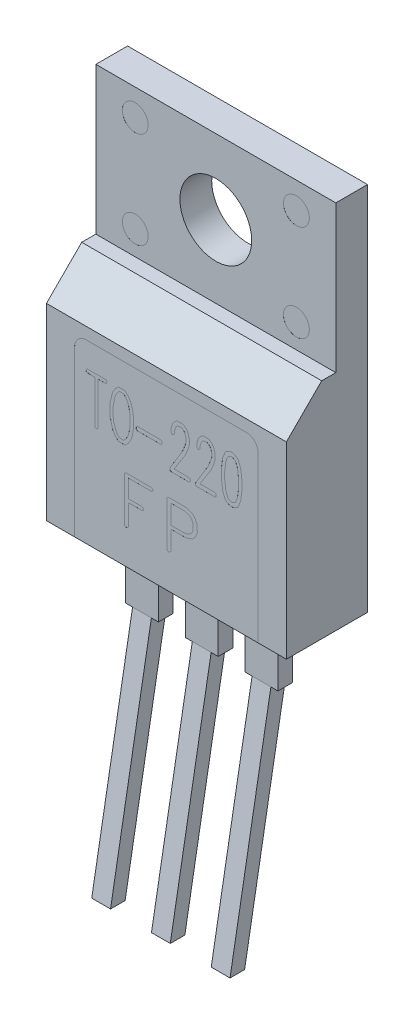
SolidWorks part; units mm, degrees
ref_plane "Front Plane" through (0, 0, 0) normal (0, 0, 1) x (1, 0, 0)
ref_plane "Top Plane" through (0, 0, 0) normal (0, 1, 0) x (1, 0, 0)
ref_plane "Right Plane" through (0, 0, 0) normal (1, 0, 0) x (0, 0, -1)
sketch "Sketch1" plane through (0, 0, 0) normal (0, 0, 1) x (1, 0, 0)
  line L0 (0, 6.225) -> (1.959, 6.225) construction
  line L1 (-5.1, 7.875) -> (5.1, 7.875)
  line L2 (-5.1, 7.875) -> (-5.1, -7.875)
  line L3 (-5.1, -7.875) -> (5.1, -7.875)
  line L4 (5.1, 7.875) -> (5.1, -7.875)
  line L5 (-5.1, 7.875) -> (5.1, -7.875) construction
  line L6 (-5.1, -7.875) -> (5.1, 7.875) construction
  circle A0 centre (0, 4.7) radius 1.525
  point P0 (0, 0)
  dimension "D3" = 3.05
  dimension "D1" = 15.75
  dimension "D2" = 10.2
  dimension "D4" = 1.65
extrude "Boss-Extrude1" add sketch "Sketch1" along normal blind 1.35
sketch "Sketch2" plane through (0, 0, 1.35) normal (0, 0, 1) x (1, 0, 0)
  line L0 (5.1, -7.875) -> (5.1, 7.875) construction
  line L1 (-5.1, -7.875) -> (5.1, -7.875)
  line L2 (-5.1, -7.875) -> (-5.1, 1.625)
  line L3 (-5.1, 1.625) -> (5.1, 1.625)
  line L4 (5.1, -7.875) -> (5.1, 1.625)
  dimension "D1" = 9.5
extrude "Boss-Extrude2" add sketch "Sketch2" along normal blind 2.1
chamfer "Chamfer1" distance 1.5 angle 45 1 edges at (0, 1.625, 3.45)
sketch "Sketch3" plane through (0, 0, 3.45) normal (0, 0, 1) x (1, 0, 0)
  line L0 (-5.1, -7.875) -> (5.1, -7.875) construction
  line L1 (-3.9, -7.875) -> (3.9, -7.875)
  line L2 (-3.9, -7.875) -> (-3.9, -0.875)
  line L3 (-3.4, -0.375) -> (3.4, -0.375)
  line L4 (3.9, -7.875) -> (3.9, -0.875)
  line L5 (5.1, 0.125) -> (-5.1, 0.125) construction
  arc A0 (3.9, -0.875) -> (3.4, -0.375) centre (3.4, -0.875) ccw
  arc A1 (-3.9, -0.875) -> (-3.4, -0.375) centre (-3.4, -0.875) cw
  point P6 (0, -7.875)
  dimension "D3" = 0.5
  dimension "D1" = 7.8
  dimension "D2" = 0.5
extrude "Cut-Extrude1" cut sketch "Sketch3" against normal blind 0.001
sketch "Sketch4" plane through (0, -7.875, 0) normal (0, -1, 0) x (1, 0, 0)
  line L0 (0, 3.449) -> (0, 0) construction
  line L1 (-3.9, 3.449) -> (3.9, 3.449) construction
  line L2 (-5.1, 0) -> (5.1, 0) construction
  line L3 (-1.84, 1.329) -> (-3.24, 1.329)
  line L4 (-0.7, 1.949) -> (0.7, 1.949)
  line L5 (-0.7, 1.949) -> (-0.7, 1.329)
  line L6 (-0.7, 1.329) -> (0.7, 1.329)
  line L7 (0.7, 1.949) -> (0.7, 1.329)
  line L8 (-0.7, 1.949) -> (0.7, 1.329) construction
  line L9 (-0.7, 1.329) -> (0.7, 1.949) construction
  line L10 (1.84, 1.949) -> (3.24, 1.949)
  line L11 (1.84, 1.949) -> (1.84, 1.329)
  line L12 (1.84, 1.329) -> (3.24, 1.329)
  line L13 (3.24, 1.949) -> (3.24, 1.329)
  line L14 (1.84, 1.949) -> (3.24, 1.329) construction
  line L15 (1.84, 1.329) -> (3.24, 1.949) construction
  line L16 (-3.24, 1.949) -> (-3.24, 1.329)
  line L17 (-1.84, 1.949) -> (-3.24, 1.949)
  line L18 (-1.84, 1.949) -> (-1.84, 1.329)
  point P6 (0, 1.639)
  point P11 (2.54, 1.639)
  dimension "D1" = 1.4
  dimension "D2" = 0.62
  dimension "D3" = 1.5
  dimension "D4" = 2.54
extrude "Boss-Extrude3" add sketch "Sketch4" along normal blind 2.85
sketch "Sketch8" plane through (0, 0, 0) normal (1, 0, 0) x (0, 0, -1)
  line L0 (-1.639, -10.725) -> (-3.3755, -20.5731)
  line L1 (-1.329, -10.725) -> (-1.949, -10.725) construction
  line L2 (-1.639, -10.725) -> (-1.639, -19.2494) construction
  dimension "D1" = 10
  dimension "D2" = 10
sketch "Sketch5" plane through (0, -10.725, 0) normal (0, -1, 0) x (1, 0, 0)
  line L0 (-1.84, 1.949) -> (-3.24, 1.949) construction
  line L1 (-2.94, 1.329) -> (-2.14, 1.329)
  line L2 (-2.94, 1.329) -> (-2.94, 1.949)
  line L3 (-2.94, 1.949) -> (-2.14, 1.949)
  line L4 (-2.14, 1.329) -> (-2.14, 1.949)
  line L5 (-2.94, 1.329) -> (-2.14, 1.949) construction
  line L6 (-2.94, 1.949) -> (-2.14, 1.329) construction
  line L7 (-3.24, 1.329) -> (-1.84, 1.329) construction
  line L8 (0, 0) -> (0, 3.449) construction
  line L9 (-3.9, 3.449) -> (3.9, 3.449) construction
  line L10 (2.94, 1.949) -> (2.14, 1.949)
  line L11 (2.14, 1.329) -> (2.14, 1.949)
  line L12 (2.94, 1.329) -> (2.14, 1.329)
  line L13 (2.94, 1.329) -> (2.94, 1.949)
  line L14 (-0.7, 1.329) -> (0.7, 1.329) construction
  line L15 (-0.4, 1.949) -> (0.4, 1.949)
  line L16 (-0.4, 1.949) -> (-0.4, 1.329)
  line L17 (-0.4, 1.329) -> (0.4, 1.329)
  line L18 (0.4, 1.949) -> (0.4, 1.329)
  line L19 (-0.4, 1.949) -> (0.4, 1.329) construction
  line L20 (-0.4, 1.329) -> (0.4, 1.949) construction
  line L21 (0.7, 1.949) -> (-0.7, 1.949) construction
  point P0 (-2.54, 1.639)
  point P18 (0, 1.639)
  point P28 (-2.54, 1.949)
  dimension "D1" = 0.8
extrude "Boss-Extrude4" add sketch "Sketch5" along direction (0, -0.9848, 0.1736) on the side of the normal blind 10
sketch "Sketch6" plane through (0, 0, 3.449) normal (0, 0, 1) x (1, 0, 0)
  line L0 (-3.9, -3.375) -> (3.9, -3.375) construction
  line L1 (-3.9, -6.375) -> (3.9, -6.375) construction
  line L2 (3.4, -0.375) -> (-3.4, -0.375) construction
  line L3 (-3.9, -0.875) -> (-3.9, -7.875) construction
  text T0 "ТО-220" font "SWSimp" height 2
  text T1 "FP" font "SWSimp" height 2
  point P4 (0, -3.375)
  dimension "D1" = 3
  dimension "D2" = 3
extrude "Cut-Extrude2" cut sketch "Sketch6" against normal blind 0.001
sketch "Sketch7" plane through (0, 0, 1.35) normal (0, 0, 1) x (1, 0, 0)
  line L0 (0, 6.75) -> (0, 2.65) construction
  line L1 (-3.425, 6.75) -> (3.425, 6.75) construction
  line L2 (-3.425, 6.75) -> (-3.425, 2.65) construction
  line L3 (-3.425, 2.65) -> (3.425, 2.65) construction
  line L4 (3.425, 6.75) -> (3.425, 2.65) construction
  line L5 (-3.425, 6.75) -> (3.425, 2.65) construction
  line L6 (-3.425, 2.65) -> (3.425, 6.75) construction
  line L7 (3.425, 4.7) -> (-3.425, 4.7) construction
  circle A0 centre (-3.425, 6.75) radius 0.55
  circle A1 centre (3.425, 6.75) radius 0.55
  circle A2 centre (-3.425, 2.65) radius 0.55
  circle A3 centre (3.425, 2.65) radius 0.55
  point P0 (0, 4.7)
  dimension "D3" = 1.1
  dimension "D1" = 4.1
  dimension "D2" = 6.85
extrude "Cut-Extrude3" cut sketch "Sketch7" against normal blind 0.001
